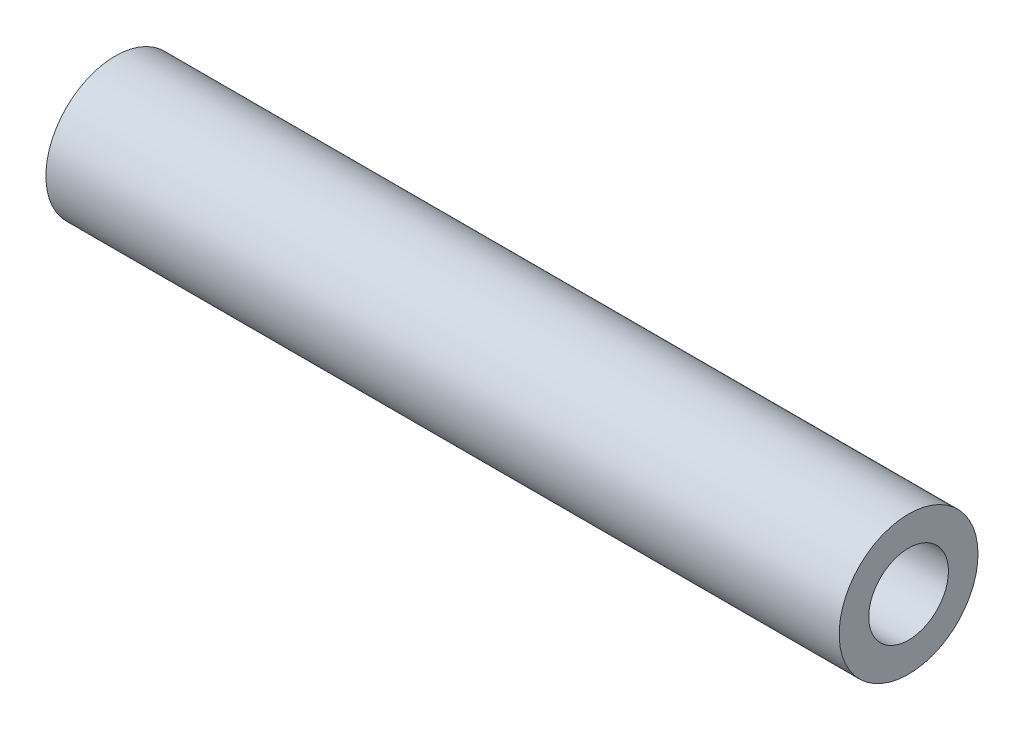
SolidWorks part; units mm, degrees
material "6061-T6 (SS)"
ref_plane "Front Plane" through (0, 0, 0) normal (0, 0, 1) x (1, 0, 0)
ref_plane "Top Plane" through (0, 0, 0) normal (0, 1, 0) x (1, 0, 0)
ref_plane "Right Plane" through (0, 0, 0) normal (1, 0, 0) x (0, 0, -1)
sketch "Sketch1" plane through (0, 0, 0) normal (1, 0, 0) x (0, 0, -1)
  circle A0 centre (0, 0) radius 2.5527
  circle A1 centre (0, 0) radius 4.445
  dimension "D1" = 5.1054
  dimension "D2" = 8.89
extrude "Boss-Extrude1" add sketch "Sketch1" along normal mid plane 50.8
